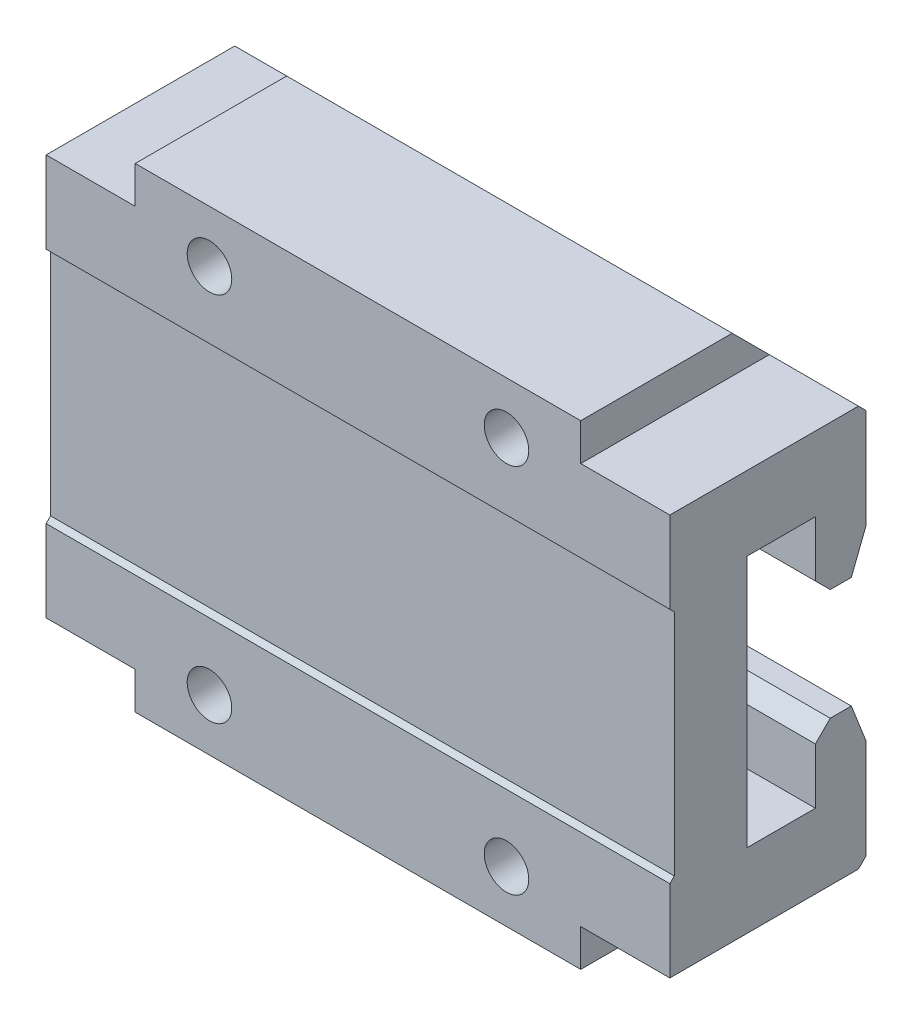
SolidWorks part; units mm, degrees
material "6061 Alloy"
ref_plane "Front Plane" through (0, 0, 0) normal (0, 0, 1) x (1, 0, 0)
ref_plane "Top Plane" through (0, 0, 0) normal (0, 1, 0) x (1, 0, 0)
ref_plane "Right Plane" through (0, 0, 0) normal (1, 0, 0) x (0, 0, -1)
sketch "Sketch1" plane through (0, 0, 0) normal (0, 0, 1) x (1, 0, 0)
  line L0 (0, 29.5) -> (6, 29.5)
  line L1 (6, 0) -> (36, 0)
  line L2 (0, 2.5) -> (0, 29.5)
  line L3 (6, 32) -> (36, 32)
  line L4 (42, 2.5) -> (42, 29.5)
  line L5 (6, 29.5) -> (6, 32)
  line L6 (0, 2.5) -> (6, 2.5)
  line L7 (6, 2.5) -> (6, 0)
  line L8 (36, 0) -> (36, 2.5)
  line L9 (36, 2.5) -> (42, 2.5)
  line L10 (42, 29.5) -> (36, 29.5)
  line L11 (36, 29.5) -> (36, 32)
  dimension "D1" = 6
  dimension "D2" = 6
  dimension "D3" = 30
  dimension "D4" = 2.5
  dimension "D5" = 27
  dimension "D6" = 32
extrude "Boss-Extrude1" add sketch "Sketch1" along normal blind 13.2 contours L2 L0 L5 L3 L11 L10 L4 L9 L8 L1 L7 L6
sketch "Sketch3" plane through (0, 0, 0) normal (1, 0, 0) x (0, 0, -1)
  line L0 (-2.4, 19.75) -> (0, 19.75)
  line L1 (-8, 24.5) -> (-3.4, 24.5)
  line L2 (-8, 24.5) -> (-8, 7.5)
  line L3 (-8, 7.5) -> (-3.4, 7.5)
  line L4 (-3.4, 24.5) -> (-3.4, 20.75)
  line L5 (0, 2.5) -> (0, 29.5) construction
  line L6 (0, 19.75) -> (0, 12.25)
  line L7 (0, 12.25) -> (-2.4, 12.25)
  line L8 (-3.4, 11.25) -> (-3.4, 7.5)
  line L9 (-8, 16) -> (-13.2, 16) construction
  line L10 (-13.2, 2.5) -> (-13.2, 29.5) construction
  line L11 (-2.4, 12.25) -> (-3.4, 11.25)
  line L12 (-3.4, 20.75) -> (-2.4, 19.75)
  point P4 (-3.4, 19.75)
  point P10 (-3.4, 12.25)
  dimension "D1" = 17
  dimension "D2" = 4.75
  dimension "D3" = 4.75
  dimension "D4" = 5.2
  dimension "D5" = 4.6
extrude "Cut-Extrude4" cut sketch "Sketch3" along normal through all
sketch "Sketch4" plane through (0, 0, 0) normal (1, 0, 0) x (0, 0, -1)
  line L0 (-13.2, 24) -> (-12.9, 23.7)
  line L1 (-13.2, 2.5) -> (-13.2, 29.5) construction
  line L2 (-12.9, 23.7) -> (-12.9, 8.3)
  line L3 (-12.9, 8.3) -> (-13.2, 8)
  line L4 (-13.2, 8) -> (-13.2, 24)
  line L5 (-12.9, 16) -> (-8, 16) construction
  line L6 (-8, 24.5) -> (-8, 7.5) construction
  line L7 (0, 3) -> (-3, 0)
  line L8 (0, 2.5) -> (0, 12.25) construction
  line L9 (-13.2, 0) -> (0, 0) construction
  line L10 (-3, 0) -> (0, 0)
  line L11 (0, 0) -> (0, 3)
  line L12 (0, 32) -> (0, 29)
  line L13 (-3, 32) -> (0, 32)
  line L14 (0, 29) -> (-3, 32)
  line L15 (-0.98, 12.25) -> (0, 9.75)
  line L16 (-2.4, 12.25) -> (0, 12.25) construction
  line L17 (0, 9.75) -> (0, 12.25)
  line L18 (0, 12.25) -> (-0.98, 12.25)
  line L19 (-0.98, 19.75) -> (0, 22.25)
  line L20 (0, 22.25) -> (0, 19.75)
  line L21 (0, 19.75) -> (-0.98, 19.75)
  dimension "D1" = 0.3
  dimension "D2" = 0.3
  dimension "D3" = 16
  dimension "D4" = 0.3
  dimension "D5" = 3
  dimension "D6" = 3
  dimension "D7" = 0.98
  dimension "D8" = 2.5
extrude "Cut-Extrude5" cut sketch "Sketch4" along normal through all
sketch "Sketch5" plane through (0, 0, 13.2) normal (0, 0, 1) x (1, 0, 0)
  line L0 (0, 24) -> (0, 29.5) construction
  line L1 (6, 32) -> (36, 32) construction
  circle A0 centre (11, 28.5) radius 1.5
  circle A1 centre (31, 28.5) radius 1.5
  circle A2 centre (31, 3.5) radius 1.5
  circle A3 centre (11, 3.5) radius 1.5
  dimension "D3" = 3
  dimension "D6" = 20
  dimension "D7" = 25
  dimension "D1" = 11
  dimension "D2" = 3.5
  dimension "D4" = 2
  dimension "D5" = 2
extrude "Cut-Extrude6" cut sketch "Sketch5" against normal through all
sketch "Sketch6" plane through (0, 0, 0) normal (0, 0, -1) x (-1, 0, 0)
  circle A0 centre (-31, 28.5) radius 3
  arc A1 (-32.4142, 29) -> (-29.5858, 29) centre (-31, 28.5) ccw construction
  circle A2 centre (-11, 28.5) radius 3
  circle A3 centre (-11, 3.5) radius 3
  circle A4 centre (-31, 3.5) radius 3
  arc A5 (-9.5858, 3) -> (-12.4142, 3) centre (-11, 3.5) ccw construction
  arc A6 (-12.4142, 29) -> (-9.5858, 29) centre (-11, 28.5) ccw construction
  dimension "D1" = 6
  dimension "D2" = 2
  dimension "D3" = 2
extrude "Cut-Extrude7" cut sketch "Sketch6" against normal blind 2
